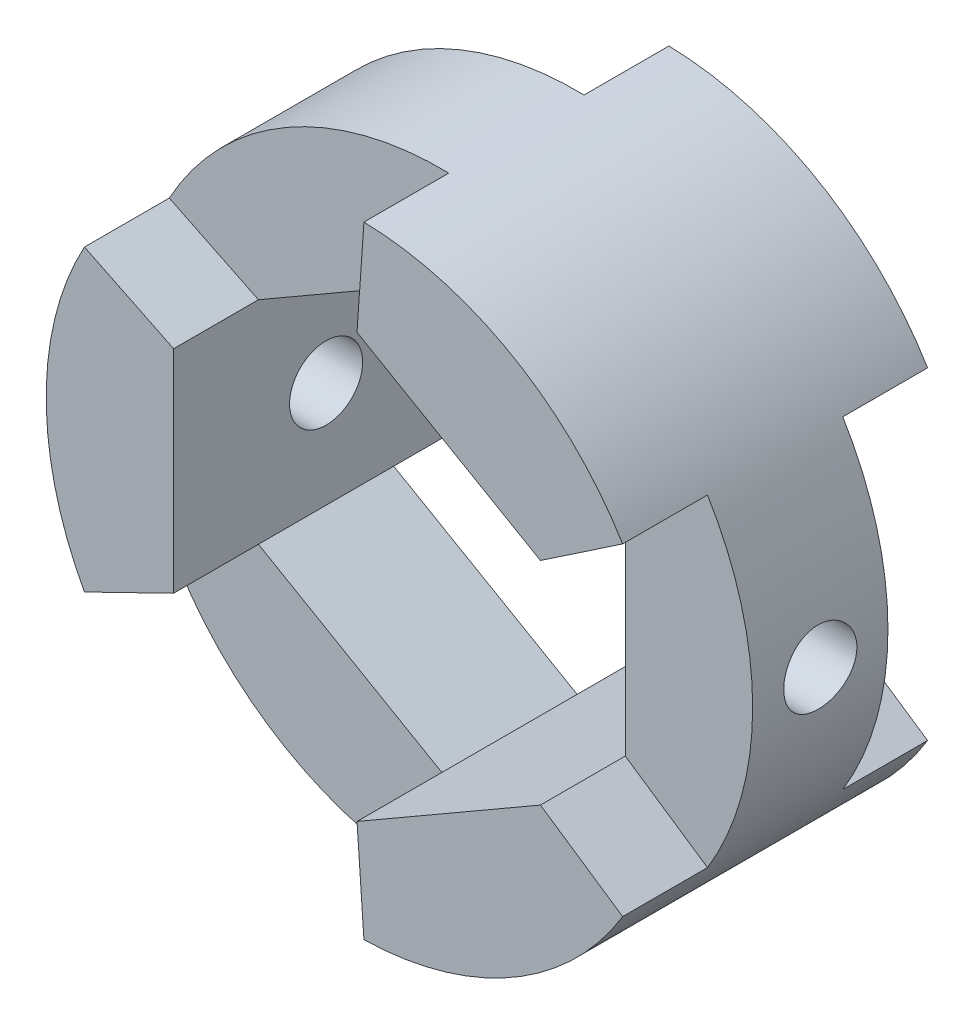
SolidWorks part; units mm, degrees
ref_plane "Front Plane" through (0, 0, 0) normal (0, 0, 1) x (1, 0, 0)
ref_plane "Top Plane" through (0, 0, 0) normal (0, 1, 0) x (1, 0, 0)
ref_plane "Right Plane" through (0, 0, 0) normal (1, 0, 0) x (0, 0, -1)
ref_plane "Plane1" through (0, 0, 0) normal (0, -1, 0) x (1, 0, 0)
sketch "Sketch1" plane through (0, 0, 0) normal (0, -1, 0) x (1, 0, 0)
  line L0 (13.4937, 6.6199) -> (0, 6.6199)
  line L1 (0, 6.6199) -> (0, -2.9369)
  line L2 (0, -2.9369) -> (13.4937, -2.9369)
  line L3 (13.4937, -2.9369) -> (13.4937, 6.6199)
  line L4 (0, 6.6199) -> (0, -2.9369) construction
revolve "Revolve1" add sketch "Sketch1" angle 360 about L4
sketch "Sketch2" plane through (0, 0, 6.6199) normal (0, 0, 1) x (1, 0, 0)
  line L0 (11.5328, 7.0053) -> (1.147, 0)
  line L1 (1.147, 0) -> (11.5328, -7.0053)
  arc A0 (11.5328, -7.0053) -> (11.5328, 7.0053) centre (0, 0) ccw
extrude "Cut-Extrude1" cut sketch "Sketch2" against normal blind 3.683
sketch "Sketch3" plane through (0, 0, 6.6199) normal (0, 0, 1) x (1, 0, 0)
  line L0 (-0.643, 0) -> (0.3004, 13.4904)
  line L1 (0.3004, -13.4904) -> (-0.643, 0)
  arc A0 (0.3004, 13.4904) -> (0.3004, -13.4904) centre (0, 0) ccw
extrude "Cut-Extrude2" cut sketch "Sketch3" against normal blind 3.683
sketch "Sketch4" plane through (0, 0, -2.9369) normal (0, 0, -1) x (-1, 0, 0)
  line L0 (-7.9629, -4.5974) -> (0, -9.1948)
  line L1 (0, -9.1948) -> (7.9629, -4.5974)
  line L2 (7.9629, -4.5974) -> (7.9629, 4.5974)
  line L3 (7.9629, 4.5974) -> (0, 9.1948)
  line L4 (0, 9.1948) -> (-7.9629, 4.5974)
  line L5 (-7.9629, 4.5974) -> (-7.9629, -4.5974)
extrude "Cut-Extrude3" cut sketch "Sketch4" against normal through all
sketch "Sketch5" plane through (0, 0, 2.9369) normal (0, 0, 1) x (1, 0, 0)
  line L0 (-11.8332, 6.4851) -> (-7.9629, 4.5974)
  line L1 (-7.9629, 4.5974) -> (-7.9629, -4.5974)
  line L2 (-7.9629, -4.5974) -> (-11.8332, -6.4851)
  arc A0 (-11.8332, -6.4851) -> (-11.8332, 6.4851) centre (0, 0) cw
extrude "Boss-Extrude1" add sketch "Sketch5" along normal blind 3.683
sketch "Sketch6" plane through (0, 0, -2.9369) normal (0, 0, -1) x (-1, 0, 0)
  line L0 (0, 9.1948) -> (-7.9629, 4.5974)
  line L1 (-7.9629, 4.5974) -> (-11.5328, 7.0053)
  line L2 (-0.3004, 13.4904) -> (0, 9.1948)
  arc A0 (-11.5328, 7.0053) -> (-0.3004, 13.4904) centre (0, 0) cw
extrude "Boss-Extrude2" add sketch "Sketch6" along normal blind 3.683
sketch "Sketch7" plane through (0, 0, -2.9369) normal (0, 0, -1) x (-1, 0, 0)
  line L0 (11.8332, -6.4851) -> (7.9629, -4.5974)
  line L1 (7.9629, -4.5974) -> (7.9629, 4.5974)
  line L2 (7.9629, 4.5974) -> (11.8332, 6.4851)
  arc A0 (11.8332, 6.4851) -> (11.8332, -6.4851) centre (0, 0) cw
extrude "Boss-Extrude3" add sketch "Sketch7" along normal blind 3.683
sketch "Sketch8" plane through (0, 0, -2.9369) normal (0, 0, -1) x (-1, 0, 0)
  line L0 (-11.5328, -7.0053) -> (-7.9629, -4.5974)
  line L1 (-7.9629, -4.5974) -> (0, -9.1948)
  line L2 (0, -9.1948) -> (-0.3004, -13.4904)
  arc A0 (-0.3004, -13.4904) -> (-11.5328, -7.0053) centre (0, 0) cw
extrude "Boss-Extrude4" add sketch "Sketch8" along normal blind 3.683
hole_wizard "M2 Clearance Hole1" positions "Sketch10" profile "Sketch9" hole size "M2" standard "ANSI Metric"
sketch "Sketch10" plane through (7.9629, 0, 0) normal (-1, 0, 0) x (0, 0, 1)
  point P0 (0, 0)
sketch "Sketch9" plane through (7.9629, 0, 0) normal (0, 1, 0) x (0, 0, 1)
  line L0 (0, 0) -> (0, 5.5309)
  line L1 (0, 5.5309) -> (1.1303, 5.5309)
  line L2 (1.1303, 5.5309) -> (1.1303, 0)
  line L5 (1.1303, 0) -> (0, 0)
  line L11 (0, -6.35) -> (0, 107.95) construction
  dimension "Thru Hole Dia." = 2.2606
  dimension "Thru Hole Depth" = 5.5309
hole_wizard "Hole1" positions "3DSketch1" profile "Sketch11" legacy
sketch3d "3DSketch1"
  point P0 (-13.4937, 0, 0)
sketch "Sketch11" plane through (-13.4937, 0, 0) normal (0, 1, 0) x (0, 0, 1)
  line L0 (0, 0) -> (0, 26.9875)
  line L1 (0, 26.9875) -> (1.5875, 26.9875)
  line L2 (1.5875, 26.9875) -> (1.5875, 3.175)
  line L3 (1.5875, 3.175) -> (2.7788, 3.175)
  line L4 (2.7788, 3.175) -> (2.7788, 0)
  line L5 (2.7788, 0) -> (0, 0)
  line L6 (0, 110) -> (0, -10) construction
  dimension "Diameter" = 3.175
  dimension "Depth" = 26.9875
  dimension "C-Bore Diameter" = 5.5575
  dimension "C-Bore Depth" = 3.175
